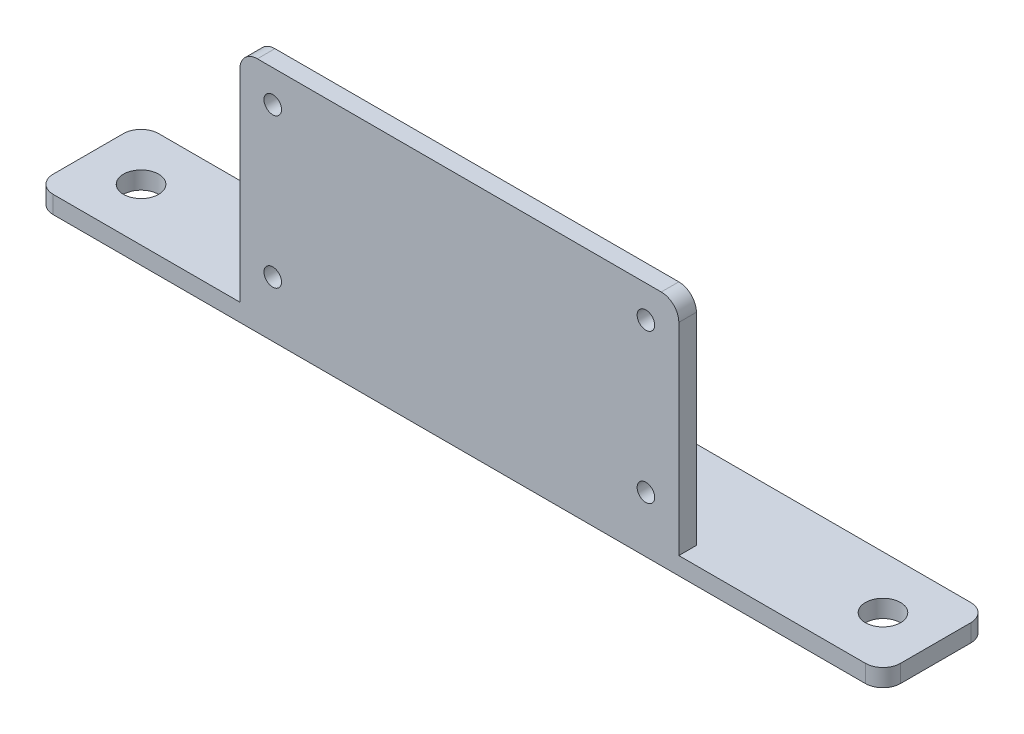
SolidWorks part; units mm, degrees
ref_plane "Front Plane" through (0, 0, 0) normal (0, 0, 1) x (1, 0, 0)
ref_plane "Top Plane" through (0, 0, 0) normal (0, 1, 0) x (1, 0, 0)
ref_plane "Right Plane" through (0, 0, 0) normal (1, 0, 0) x (0, 0, -1)
sketch "Sketch3" plane through (0, 0, 0) normal (0, 1, 0) x (1, 0, 0)
  line L0 (42.25, 0) -> (-42.25, 0)
  line L2 (48.25, 6) -> (-48.25, 6)
  line L3 (48.25, 6) -> (48.25, -6)
  line L4 (48.25, -6) -> (-48.25, -6)
  line L5 (-48.25, 6) -> (-48.25, -6)
  line L6 (48.25, 6) -> (-48.25, -6) construction
  line L7 (48.25, -6) -> (-48.25, 6) construction
  circle A0 centre (-42.25, 0) radius 2
  circle A1 centre (42.25, 0) radius 2
  circle A2 centre (0, 0) radius 2 construction
  circle A3 centre (0, 6) radius 8.7286
  point P0 (0, 0)
  point P4 (0, 0)
  dimension "D4" = 4
  dimension "D5" = 4
  dimension "D6" = 4
  dimension "D1" = 84.5
  dimension "D2" = 6
  dimension "D3" = 6
extrude "Boss-Extrude1" add sketch "Sketch3" along normal blind 2
sketch "Sketch4" plane through (0, 2, 0) normal (0, 1, 0) x (1, 0, 0)
  line L0 (0, -3.3691) -> (0, -22.5177) construction
  line L1 (0, -6) -> (0, -4)
  line L2 (48.25, -6) -> (-48.25, -6) construction
  line L3 (25, -6) -> (-25, -6)
  line L5 (25, -4) -> (-25, -4)
  line L6 (25, -4) -> (25, -6)
  line L7 (25, -6) -> (-25, -6)
  line L8 (-25, -4) -> (-25, -6)
  line L9 (25, -4) -> (-25, -6) construction
  line L10 (25, -6) -> (-25, -4) construction
  point P10 (0, -6)
  point P11 (0, -5)
  line M7 (-48.25, -6) -> (48.25, -6)
  dimension "D1" = 2
  dimension "D2" = 50
  dimension "D3" = 2
extrude "Boss-Extrude2" add sketch "Sketch4" along normal blind 25 contours L5 L8 L1 M7 | L6 L5 L1 M7
sketch "Sketch6" plane through (0, 0, 6) normal (0, 0, 1) x (1, 0, 0)
  line L0 (0, 27) -> (0, -22.6431) construction
  line L1 (-25, 27) -> (25, 27) construction
  line L2 (21.25, 23.3548) -> (-21.25, 23.3548) construction
  line L3 (-21.25, 23.3548) -> (-21.25, 6.3548) construction
  line L4 (-21.25, 6.3548) -> (21.25, 6.3548) construction
  line L5 (21.25, 6.3548) -> (21.25, 23.3548) construction
  line L6 (-21.25, 14.8548) -> (41.0631, 14.8548) construction
  circle A0 centre (21.25, 23.3548) radius 1
  circle A1 centre (-21.25, 23.3548) radius 1
  circle A2 centre (21.25, 6.3548) radius 1
  circle A3 centre (-21.25, 6.3548) radius 1
  point P8 (0, 23.3548)
  dimension "D3" = 2
  dimension "D1" = 42.5
  dimension "D2" = 17
extrude "Cut-Extrude1" cut sketch "Sketch6" against normal up to next
fillet "Fillet1" radius 2 8 edges at (25, 27, 5) (-25, 27, 5) (-48.25, 1, 6) (-48.25, 1, -6) (-8.7286, 1, -6) (8.7286, 1, -6) (48.25, 1, -6) (48.25, 1, 6)
